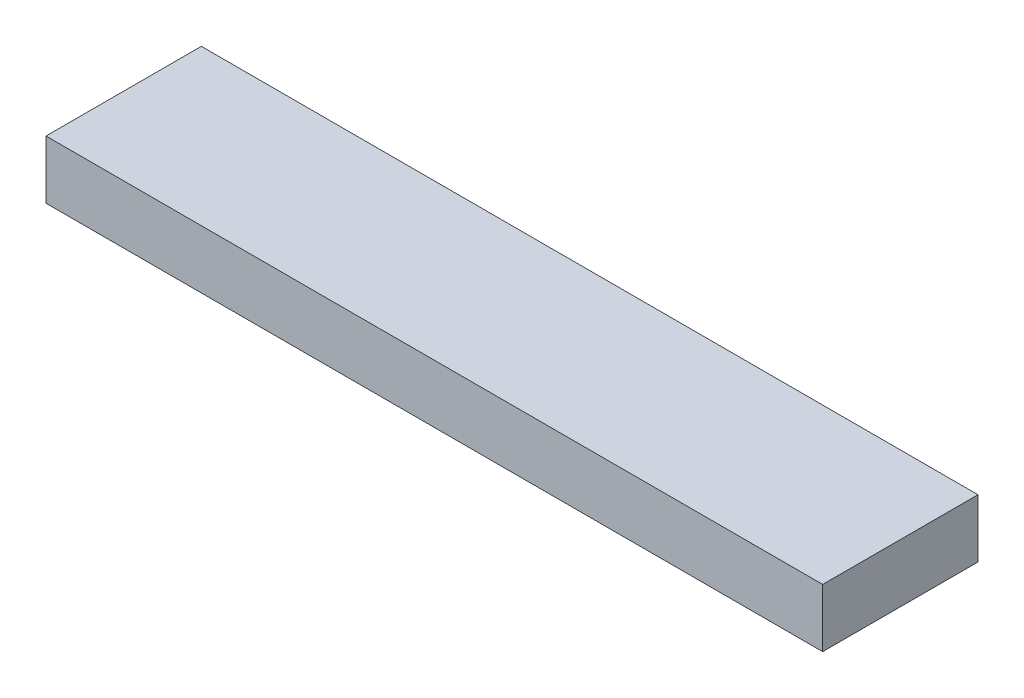
SolidWorks part; units mm, degrees
ref_plane "Front Plane" through (0, 0, 0) normal (0, 0, 1) x (1, 0, 0)
ref_plane "Top Plane" through (0, 0, 0) normal (0, 1, 0) x (1, 0, 0)
ref_plane "Right Plane" through (0, 0, 0) normal (1, 0, 0) x (0, 0, -1)
sketch "Sketch1" plane through (0, 0, 0) normal (0, 1, 0) x (1, 0, 0)
  line L1 (20, -4) -> (-20, -4)
  line L2 (20, -4) -> (20, 4)
  line L3 (20, 4) -> (-20, 4)
  line L4 (-20, -4) -> (-20, 4)
  line L5 (20, -4) -> (-20, 4) construction
  line L6 (20, 4) -> (-20, -4) construction
  point P0 (0, 0)
  dimension "D1" = 8
  dimension "D2" = 40
extrude "Boss-Extrude1" add sketch "Sketch1" along normal blind 3
